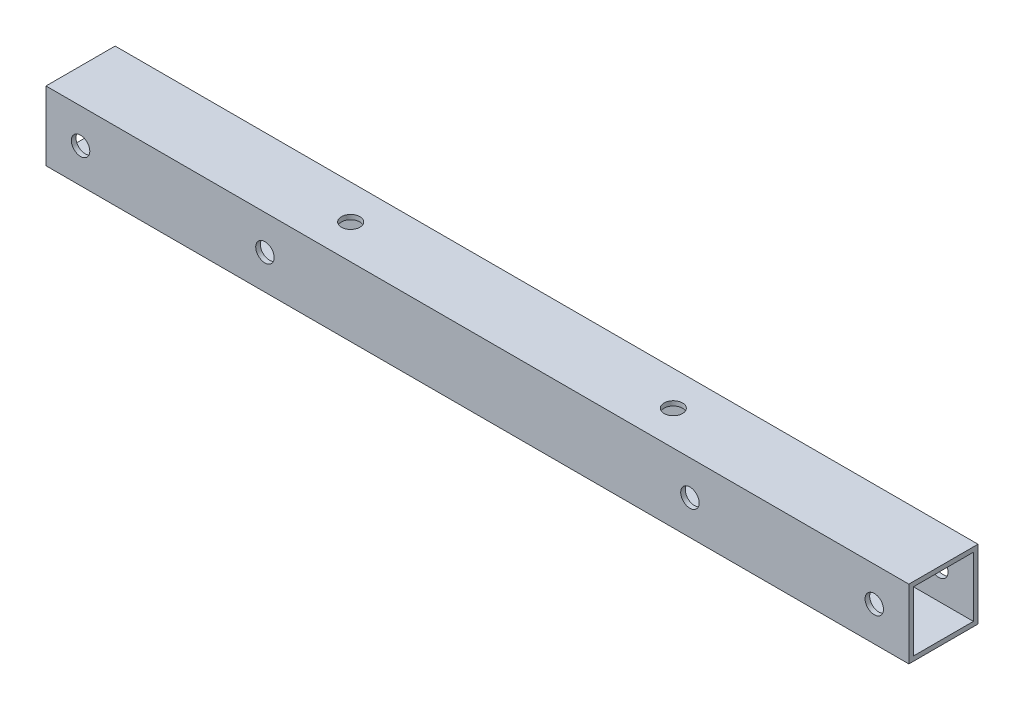
SolidWorks part; units mm, degrees
material "1060 合金"
ref_plane "正面" through (0, 0, 0) normal (0, 0, 1) x (1, 0, 0)
ref_plane "平面" through (0, 0, 0) normal (0, 1, 0) x (1, 0, 0)
ref_plane "右側面" through (0, 0, 0) normal (1, 0, 0) x (0, 0, -1)
sketch "ｽｹｯﾁ1" plane through (0, 0, 0) normal (1, 0, 0) x (0, 0, -1)
  line L1 (-7.5, -7.5) -> (7.5, -7.5)
  line L2 (-7.5, -7.5) -> (-7.5, 7.5)
  line L3 (-7.5, 7.5) -> (7.5, 7.5)
  line L4 (7.5, -7.5) -> (7.5, 7.5)
  line L5 (-7.5, -7.5) -> (7.5, 7.5) construction
  line L6 (-7.5, 7.5) -> (7.5, -7.5) construction
  point P0 (0, 0)
  dimension "D1" = 15
extrude "押し出し-薄板1" add sketch "ｽｹｯﾁ1" along normal blind 187.2 thin thin type one direction reverse wall 1
sketch "ｽｹｯﾁ2" plane through (0, 0, 7.5) normal (0, 0, 1) x (1, 0, 0)
  line L0 (7.5, 0) -> (-49992.5, 0) construction
  line L2 (93.6, 7.5) -> (93.6, -7.5) construction
  line L3 (187.2, 7.5) -> (0, 7.5) construction
  line L4 (187.2, -7.5) -> (0, -7.5) construction
  line L5 (0, 7.5) -> (0, -7.5) construction
  circle A0 centre (7.5, 0) radius 2
  circle A1 centre (47.5, 0) radius 2
  circle A2 centre (139.7, 0) radius 2
  circle A3 centre (179.7, 0) radius 2
  dimension "D1" = 7.5
  dimension "D2" = 40
  dimension "D3" = 4
  dimension "D4" = 7.5
extrude "ｶｯﾄ - 押し出し1" cut sketch "ｽｹｯﾁ2" against normal through all
sketch "ｽｹｯﾁ3" plane through (0, 7.5, 0) normal (0, 1, 0) x (1, 0, 0)
  line L0 (0, 0) -> (50000, 0) construction
  line L2 (187.2, 7.5) -> (0, 7.5) construction
  line L3 (93.6, 7.5) -> (93.6, -7.5) construction
  line L4 (187.2, -7.5) -> (0, -7.5) construction
  circle A0 centre (58.6, 0) radius 2
  circle A1 centre (128.6, 0) radius 2
  dimension "D2" = 4
  dimension "D3" = 70
  dimension "D1" = 7.5
extrude "ｶｯﾄ - 押し出し2" cut sketch "ｽｹｯﾁ3" against normal through all
